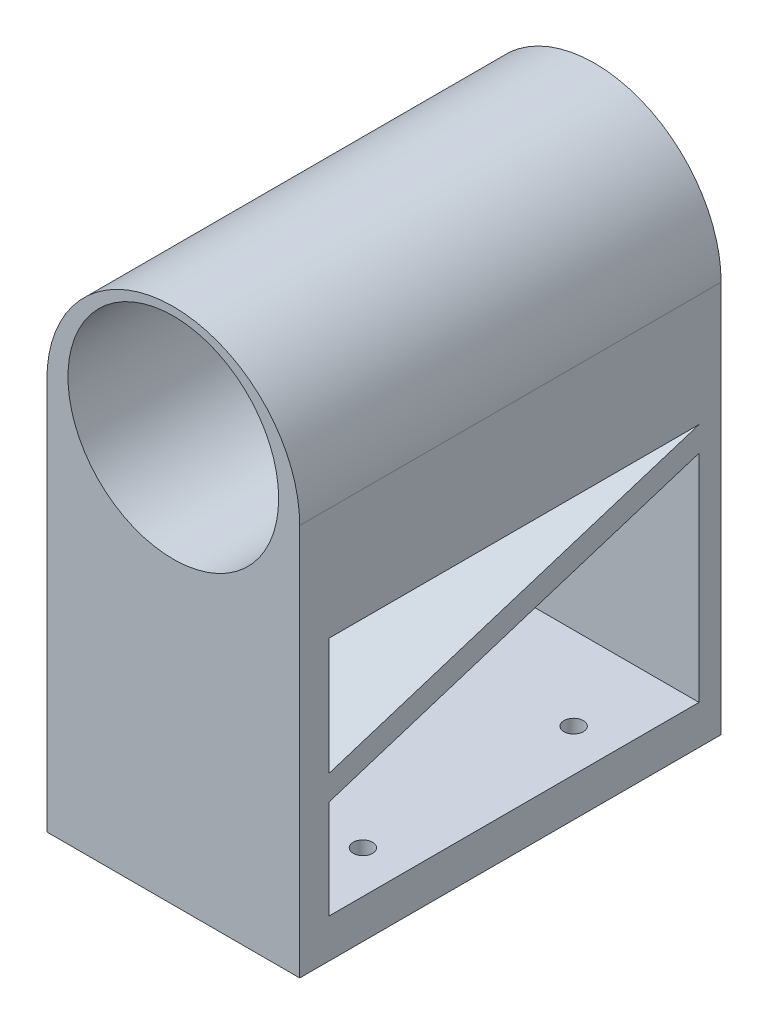
SolidWorks part; units mm, degrees
ref_plane "Front Plane" through (0, 0, 0) normal (0, 0, 1) x (1, 0, 0)
ref_plane "Top Plane" through (0, 0, 0) normal (0, 1, 0) x (1, 0, 0)
ref_plane "Right Plane" through (0, 0, 0) normal (1, 0, 0) x (0, 0, -1)
sketch "Sketch1" plane through (0, 0, 0) normal (0, 0, 1) x (1, 0, 0)
  line L2 (17.78, 16.9849) -> (17.78, -30.2591)
  line L3 (17.78, -30.2591) -> (-12.7, -30.2591)
  line L4 (-12.7, 16.9849) -> (-12.7, -30.2591)
  arc A0 (17.78, 16.9849) -> (-12.7, 16.9849) centre (2.54, 16.9849) ccw
  point P0 (0, 0)
  dimension "D1" = 30.48
  dimension "D2" = 47.244
  dimension "D3" = 47.244
extrude "Boss-Extrude1" add sketch "Sketch1" along normal blind 50.8
sketch "Sketch2" plane through (0, 0, 50.8) normal (0, 0, 1) x (1, 0, 0)
  line L0 (2.54, 28.3005) -> (2.54, 32.2249) construction
  line L1 (2.54, 32.2249) -> (2.54, -30.2591) construction
  line L2 (-12.7, -30.2591) -> (17.78, -30.2591) construction
  arc A0 (17.78, 16.9849) -> (-12.7, 16.9849) centre (2.54, 16.9849) ccw construction
  circle A1 centre (2.54, 18.5426) radius 12.7
  point P10 (0, 0)
  dimension "D1" = 25.4
extrude "Cut-Extrude1" cut sketch "Sketch2" against normal blind 50.8
sketch "Sketch4" plane through (17.78, 0, 0) normal (1, 0, 0) x (0, 0, -1)
  line L0 (-50.8, 3.4537) -> (0, 3.4537) construction
  line L1 (-50.8, -30.2591) -> (-50.8, 16.9849) construction
  line L2 (0, -30.2591) -> (0, 16.9849) construction
  line L3 (-47.247, 3.4537) -> (-2.6645, 3.4537)
  line L4 (-2.6645, 3.4537) -> (-47.247, -10.6573)
  line L5 (-47.247, -10.6573) -> (-47.247, 3.4537)
  line L6 (-47.247, -13.6454) -> (-2.6645, 0.4656)
  line L7 (-2.6645, 0.4656) -> (-2.6645, -25.5539)
  line L8 (-2.6645, -25.5539) -> (-47.247, -25.5539)
  line L9 (-47.247, -25.5539) -> (-47.247, -13.6454)
extrude "Cut-Extrude2" cut sketch "Sketch4" against normal blind 50.8
sketch "Sketch5" plane through (0, -30.2591, 0) normal (0, -1, 0) x (-1, 0, 0)
  line L0 (-2.54, 0) -> (-2.54, -50.8) construction
  line L1 (12.7, 0) -> (-17.78, 0) construction
  line L2 (12.7, -50.8) -> (-17.78, -50.8) construction
  line L3 (7.62, 0) -> (7.62, -50.8) construction
  line L4 (-12.7, 0) -> (-12.7, -50.8) construction
  line L5 (7.62, -25.4) -> (-12.7, -25.4) construction
  line L6 (7.62, -12.7) -> (-12.7, -12.7) construction
  line L7 (7.62, -38.1) -> (-12.7, -38.1) construction
  circle A0 centre (7.62, -12.7) radius 1.1667
  circle A1 centre (7.62, -38.1) radius 1.1667
  circle A2 centre (-12.7, -38.1) radius 1.1667
  circle A3 centre (-12.7, -12.7) radius 1.1667
  dimension "D1" = 10.16
  dimension "D2" = 10.16
  dimension "D3" = 12.7
  dimension "D4" = 12.7
extrude "Cut-Extrude3" cut sketch "Sketch5" against normal blind 7.62
